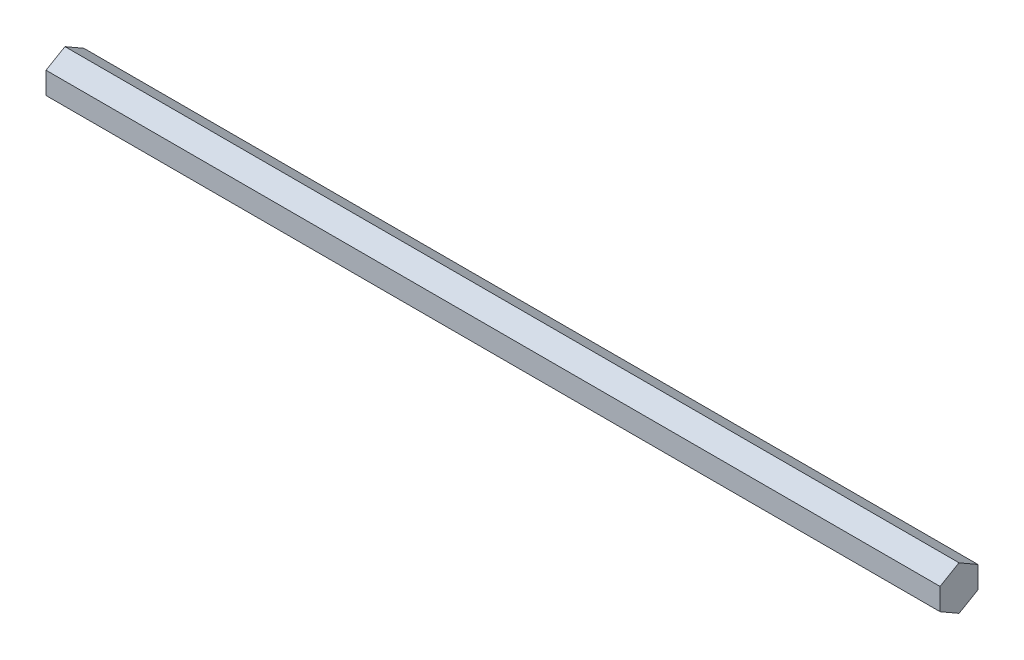
SolidWorks part; units mm, degrees
ref_plane "Front Plane" through (0, 0, 0) normal (0, 0, 1) x (1, 0, 0)
ref_plane "Top Plane" through (0, 0, 0) normal (0, 1, 0) x (1, 0, 0)
ref_plane "Right Plane" through (0, 0, 0) normal (1, 0, 0) x (0, 0, -1)
sketch "Hex Profile" plane through (0, 0, 0) normal (1, 0, 0) x (0, 0, -1)
  line L1 (4.1244, -2.3813) -> (4.1244, 2.3813)
  line L2 (4.1244, 2.3813) -> (0, 4.7625)
  line L3 (0, 4.7625) -> (-4.1244, 2.3813)
  line L4 (-4.1244, 2.3813) -> (-4.1244, -2.3813)
  line L5 (-4.1244, -2.3813) -> (0, -4.7625)
  line L6 (0, -4.7625) -> (4.1244, -2.3813)
  circle A0 centre (0, 0) radius 4.7625 construction
  dimension "D1" = 9.525
extrude "Axle" add sketch "Hex Profile" along normal blind 194.31
